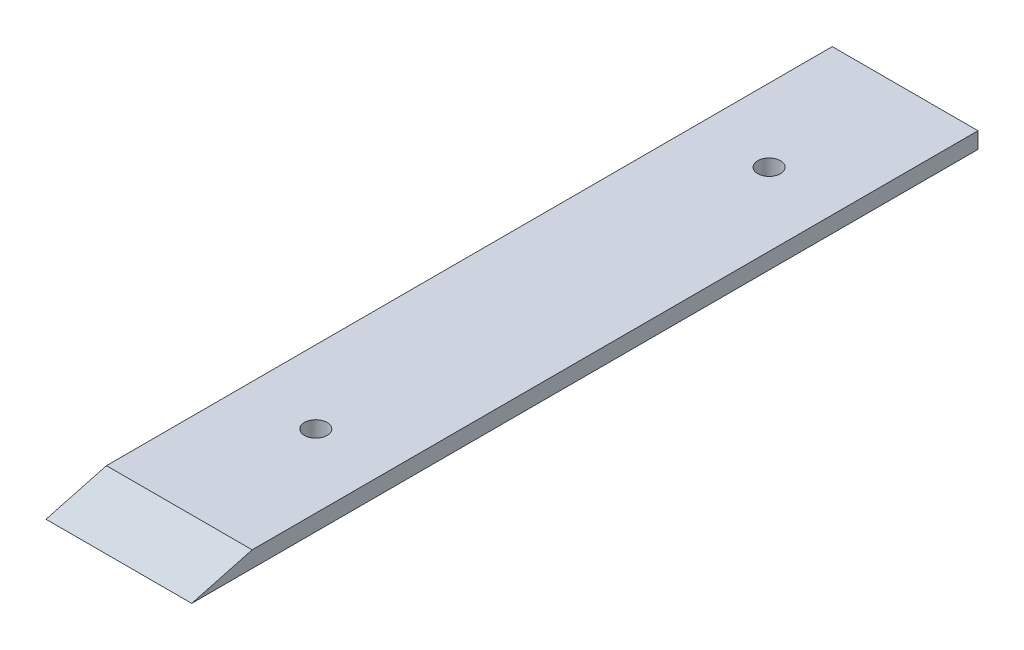
SolidWorks part; units mm, degrees
material "PE1000 Высокой плотности"
ref_plane "Спереди" through (0, 0, 0) normal (0, 0, 1) x (1, 0, 0)
ref_plane "Сверху" through (0, 0, 0) normal (0, 1, 0) x (1, 0, 0)
ref_plane "Справа" through (0, 0, 0) normal (1, 0, 0) x (0, 0, -1)
sketch "Эскиз1" plane through (0, 0, 0) normal (0, 0, 1) x (1, 0, 0)
  line L1 (-22.5, -2.5) -> (22.5, -2.5)
  line L2 (-22.5, -2.5) -> (-22.5, 2.5)
  line L3 (-22.5, 2.5) -> (22.5, 2.5)
  line L4 (22.5, -2.5) -> (22.5, 2.5)
  line L5 (-22.5, -2.5) -> (22.5, 2.5) construction
  line L6 (-22.5, 2.5) -> (22.5, -2.5) construction
  point P0 (0, 0)
  dimension "D1" = 5
  dimension "D2" = 45
extrude "Бобышка-Вытянуть1" add sketch "Эскиз1" along normal blind 242.8
sketch "Эскиз2" plane through (0, -2.5, 0) normal (0, -1, 0) x (1, 0, 0)
  line L0 (-22.5, 0) -> (22.5, 0) construction
  circle A0 centre (-5, 112) radius 15
  dimension "D1" = 30
  dimension "D2" = 112
extrude "Вырез-Вытянуть1" [suppressed] cut sketch "Эскиз2" against normal blind 10
sketch "Эскиз3" plane through (0, 2.5, 0) normal (0, 1, 0) x (1, 0, 0)
  line L0 (22.5, 0) -> (-22.5, 0) construction
  line L1 (0, 0) -> (0, -42) construction
  circle A0 centre (0, -42) radius 3.5
  circle A1 centre (0, -182) radius 3.5
  circle A2 centre (0, -322) radius 3.5
  circle A3 centre (0, -462) radius 3.5
  circle A4 centre (0, -602) radius 3.5
  circle A5 centre (0, -742) radius 3.5
  circle A6 centre (0, -882) radius 3.5
  circle A7 centre (0, -1022) radius 3.5
  circle A8 centre (0, -1162) radius 3.5
  circle A9 centre (0, -1302) radius 3.5
  dimension "D1" = 42
  dimension "D2" = 7
  dimension "D4" = 140
  dimension "D3" = 10
extrude "Вырез-Вытянуть2" cut sketch "Эскиз3" against normal through all both and the other way through all
sketch "Эскиз4" plane through (-22.5, 0, 0) normal (-1, 0, 0) x (0, 0, 1)
  line L0 (242.8, -2.5) -> (224.1397, 2.5)
  line L1 (224, 2.5) -> (0, 2.5) construction
  line L2 (224.1397, 2.5) -> (242.8, 2.5)
  line L3 (242.8, 2.5) -> (242.8, -2.5)
  line L4 (242.8, -2.5) -> (0, -2.5) construction
  line L7 (242.8, 2.5) -> (0, 2.5) construction
  line L8 (242.8, 2.5) -> (242.8, -2.5) construction
  dimension "D1" = 15
extrude "Вырез-Вытянуть3" cut sketch "Эскиз4" against normal through all both and the other way through all
